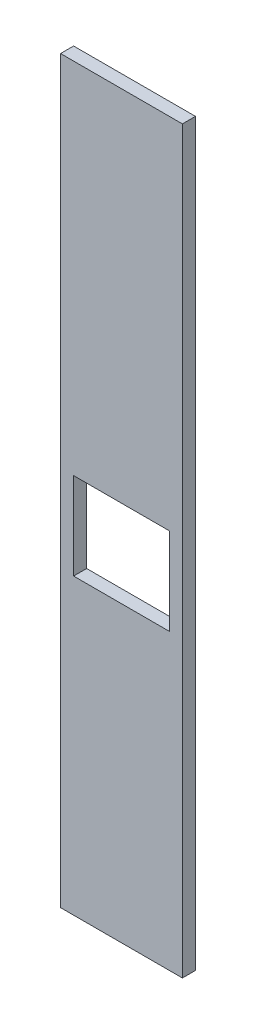
SolidWorks part; units mm, degrees
ref_plane "Plan de face" through (0, 0, 0) normal (0, 0, 1) x (1, 0, 0)
ref_plane "Plan de dessus" through (0, 0, 0) normal (0, 1, 0) x (1, 0, 0)
ref_plane "Plan de droite" through (0, 0, 0) normal (1, 0, 0) x (0, 0, -1)
sketch "Esquisse1" plane through (0, 0, 0) normal (0, 0, 1) x (1, 0, 0)
  line L1 (0, 0) -> (-56, 0)
  line L2 (0, 0) -> (0, 340)
  line L3 (0, 340) -> (-56, 340)
  line L4 (-56, 0) -> (-56, 340)
  line L5 (-6, 135) -> (-50, 135)
  line L6 (-6, 135) -> (-6, 175)
  line L7 (-6, 175) -> (-50, 175)
  line L8 (-50, 135) -> (-50, 175)
  dimension "D3" = 6
  dimension "D4" = 40
  dimension "D1" = 340
  dimension "D2" = 56
  dimension "D5" = 44
  dimension "D6" = 165
extrude "Boss.-Extru.1" add sketch "Esquisse1" along normal blind 6
